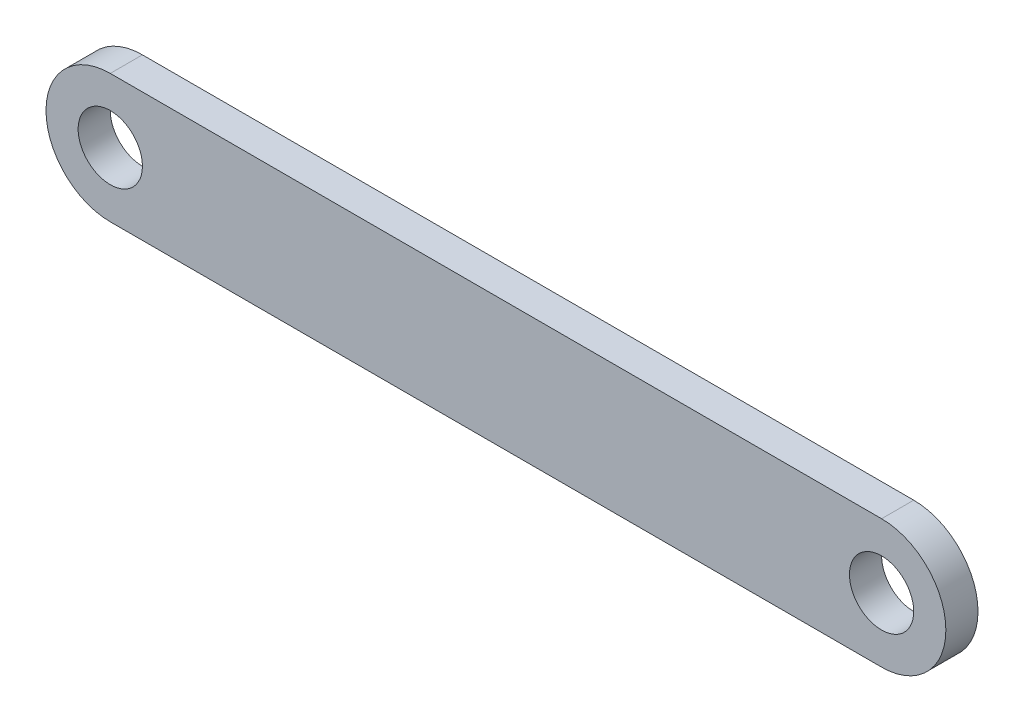
SolidWorks part; units mm, degrees
material "Plain Carbon Steel"
ref_plane "Front Plane" through (0, 0, 0) normal (0, 0, 1) x (1, 0, 0)
ref_plane "Top Plane" through (0, 0, 0) normal (0, 1, 0) x (1, 0, 0)
ref_plane "Right Plane" through (0, 0, 0) normal (1, 0, 0) x (0, 0, -1)
sketch "Sketch1" plane through (0, 0, 0) normal (0, 0, 1) x (1, 0, 0)
  line L0 (-381, 0) -> (381, 0) construction
  line L1 (-381, 63.5) -> (381, 63.5)
  line L2 (-381, -63.5) -> (381, -63.5)
  arc A0 (-381, 63.5) -> (-381, -63.5) centre (-381, 0) ccw
  arc A1 (381, -63.5) -> (381, 63.5) centre (381, 0) ccw
  point P2 (0, 0)
  dimension "D2" = 63.5
  dimension "D1" = 762
extrude "Boss-Extrude1" add sketch "Sketch1" along normal blind 31.75
sketch "Sketch2" plane through (0, 0, 31.75) normal (0, 0, 1) x (1, 0, 0)
  circle A0 centre (-381, 0) radius 31.75
  circle A1 centre (381, 0) radius 31.75
  dimension "D1" = 63.5
extrude "Cut-Extrude1" cut sketch "Sketch2" against normal through all
